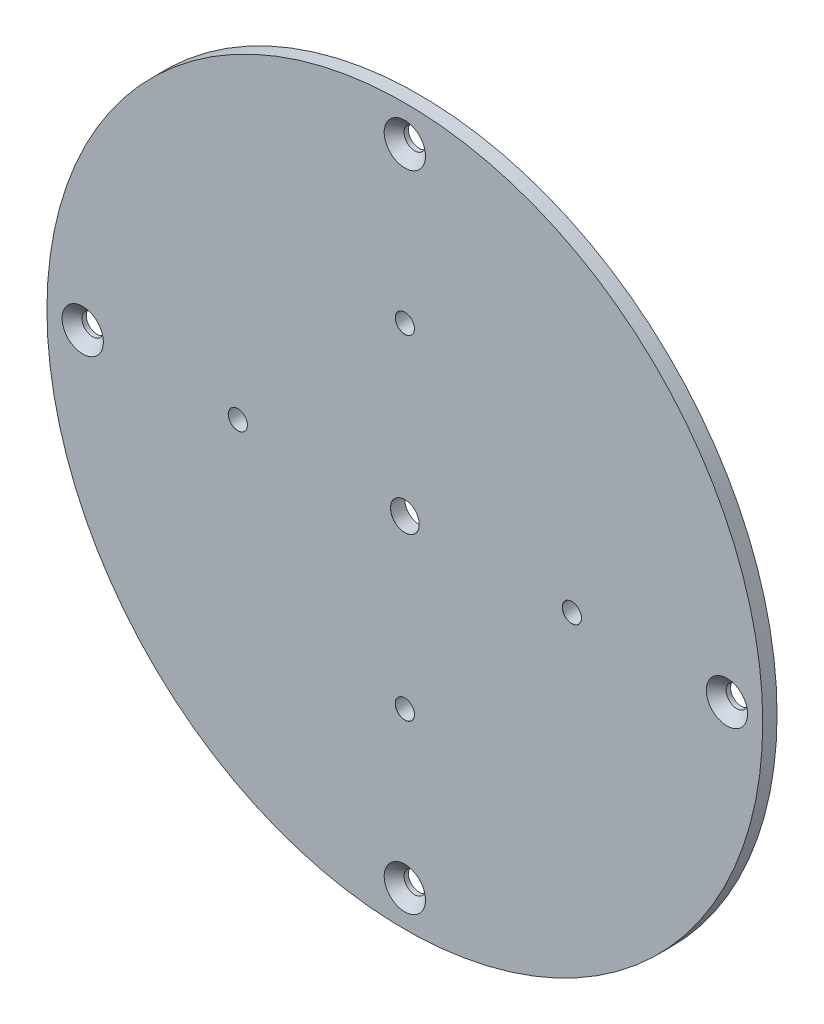
SolidWorks part; units mm, degrees
ref_plane "Płaszczyzna przednia" through (0, 0, 0) normal (0, 0, 1) x (1, 0, 0)
ref_plane "Płaszczyzna górna" through (0, 0, 0) normal (0, 1, 0) x (1, 0, 0)
ref_plane "Płaszczyzna prawa" through (0, 0, 0) normal (1, 0, 0) x (0, 0, -1)
sketch "Szkic1" plane through (0, 0, 0) normal (0, 0, 1) x (1, 0, 0)
  circle A0 centre (0, 0) radius 150
  dimension "D1" = 300
extrude "Dodanie-wyciągnięcie1" add sketch "Szkic1" along normal blind 6
sketch "Szkic2" plane through (0, 0, 6) normal (0, 0, 1) x (1, 0, 0)
  line L0 (0, 0) -> (105.8893, 0) construction
  line L1 (0, 0) -> (0, 82.1396) construction
  point P1 (0, 70)
  point P3 (0, 0)
  point P6 (0, -70)
  dimension "D2" = 70
hole_wizard "Otwory ustalające Ø8.0mm1" positions "Szkic3" profile "Szkic4" hole size "Ø8.0" standard "Ansi Metric" end condition through all
sketch "Szkic3" plane through (0, 0, 6) normal (0, 0, 1) x (1, 0, 0)
  point P0 (0, 70)
  point P3 (0, -70)
  point P6 (-70, 0)
  point P8 (70, 0)
  dimension "D1" = 70
  dimension "D2" = 70
sketch "Szkic4" plane through (0, 70, 6) normal (1, 0, 0) x (0, -1, 0)
  line L0 (0, 0) -> (0, 6)
  line L1 (0, 6) -> (4, 6)
  line L2 (4, 6) -> (4, 0.025)
  line L3 (4, 0.025) -> (4.025, 0)
  line L5 (4.025, 0) -> (0, 0)
  line L6 (-4, 0.025) -> (-4.025, 0) construction
  line L11 (0, -6.35) -> (0, 107.95) construction
  dimension "Średnica otworu na wylot" = 8
  dimension "Głębokość otworu na wylot" = 6
  dimension "Średnica zewnętrznego pogłębienia stożkowego" = 8.05
  dimension "Kąt zewnętrznego pogłębienia stożkowego" = 90
hole_wizard "Otwory ustalające Ø12.0mm1" positions "Szkic5" profile "Szkic6" hole size "Ø12.0" standard "Ansi Metric" end condition through all
sketch "Szkic5" plane through (0, 0, 6) normal (0, 0, 1) x (1, 0, 0)
  point P0 (0, 0)
sketch "Szkic6" plane through (0, 0, 6) normal (1, 0, 0) x (0, -1, 0)
  line L0 (0, 0) -> (0, 6)
  line L1 (0, 6) -> (6, 6)
  line L2 (6, 6) -> (6, 0.025)
  line L3 (6, 0.025) -> (6.025, 0)
  line L5 (6.025, 0) -> (0, 0)
  line L6 (-6, 0.025) -> (-6.025, 0) construction
  line L11 (0, -6.35) -> (0, 107.95) construction
  dimension "Średnica otworu na wylot" = 12
  dimension "Głębokość otworu na wylot" = 6
  dimension "Średnica zewnętrznego pogłębienia stożkowego" = 12.05
  dimension "Kąt zewnętrznego pogłębienia stożkowego" = 90
sketch "Szkic7" plane through (0, 0, 6) normal (0, 0, 1) x (1, 0, 0)
  point P0 (0, 135)
  point P5 (135, 0)
  point P6 (0, -135)
  point P7 (-135, 0)
  point P8 (0, 0)
  dimension "D1" = 135
  dimension "D2" = 4
hole_wizard "Pogłębienie stożkowe pod M8 wkręt do części metalowych z łbem soczewkowym1" positions "Szkic8" profile "Szkic10" countersink size "M8" standard "Ansi Metric" end condition through all
sketch "Szkic8" plane through (0, 0, 6) normal (0, 0, 1) x (1, 0, 0)
  point P0 (0, 135)
  point P3 (135, 0)
  point P6 (0, -135)
  point P9 (-135, 0)
sketch "Szkic10" plane through (0, 135, 6) normal (1, 0, 0) x (0, -1, 0)
  line L0 (0, 0) -> (0, 6)
  line L1 (0, 6) -> (4.5, 6)
  line L2 (4.5, 6) -> (4.5, 4.15)
  line L3 (4.5, 4.15) -> (8.65, 0)
  line L5 (8.65, 0) -> (0, 0)
  line L6 (-4.5, 4.15) -> (-8.65, 0) construction
  line L11 (0, -6.35) -> (0, 107.95) construction
  dimension "Średnica otworu na wylot" = 9
  dimension "Głębokość otworu na wylot" = 6
  dimension "Średnica zewnętrznego pogłębienia stożkowego" = 17.3
  dimension "Kąt zewnętrznego pogłębienia stożkowego" = 90
